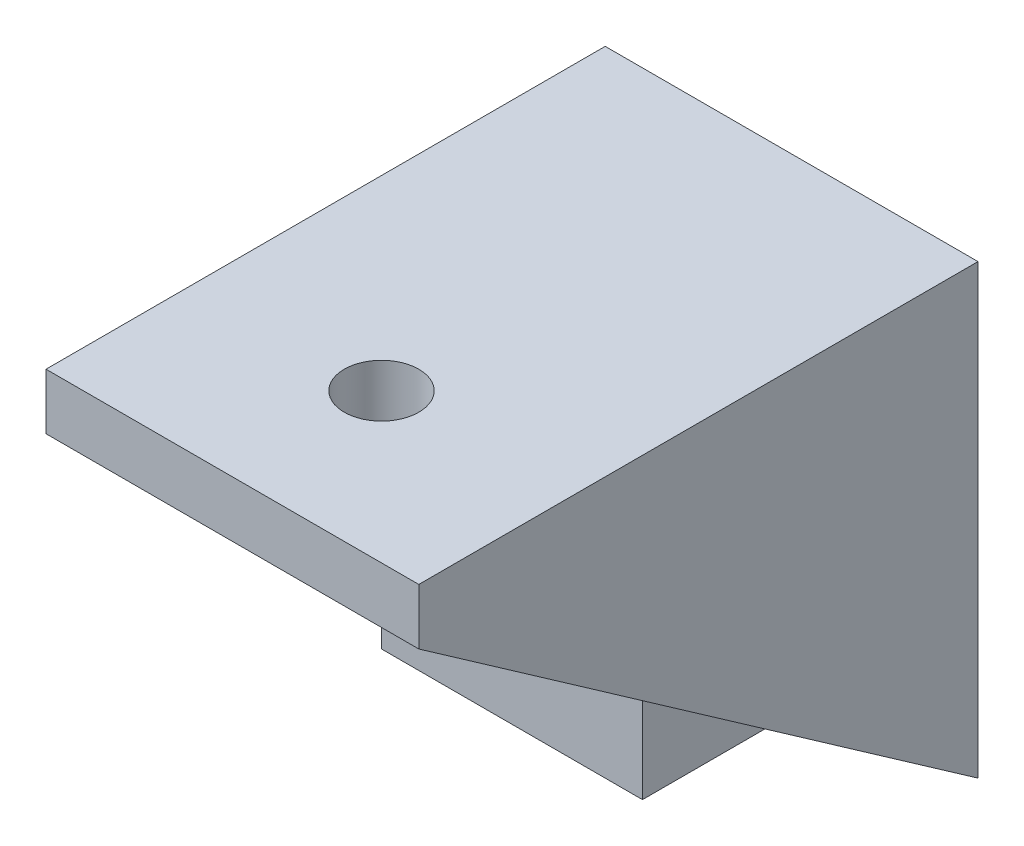
SolidWorks part; units mm, degrees
ref_plane "Front" through (0, 0, 0) normal (0, 0, 1) x (1, 0, 0)
ref_plane "Top" through (0, 0, 0) normal (0, 1, 0) x (1, 0, 0)
ref_plane "Right" through (0, 0, 0) normal (1, 0, 0) x (0, 0, -1)
sketch "Sketch1" plane through (0, 0, 0) normal (0, 0, 1) x (1, 0, 0)
  line L1 (-10, -12) -> (10, -12)
  line L2 (-10, -12) -> (-10, 12)
  line L3 (-10, 12) -> (10, 12)
  line L4 (10, -12) -> (10, 12)
  line L5 (-10, -12) -> (10, 12) construction
  line L6 (-10, 12) -> (10, -12) construction
  point P0 (0, 0)
  dimension "D1" = 24
  dimension "D2" = 20
extrude "Boss-Extrude1" add sketch "Sketch1" along normal blind 30
sketch "Sketch2" plane through (10, 0, 0) normal (1, 0, 0) x (0, 0, -1)
  line L0 (0, -12) -> (-30, 9)
  line L1 (-30, -12) -> (-30, 12) construction
  line L2 (-30, 12) -> (0, 12) construction
  line L3 (-30, 9) -> (-30, -12)
  line L4 (-30, -12) -> (0, -12)
  dimension "D1" = 3
extrude "Cut-Extrude1" cut sketch "Sketch2" against normal through all
sketch "Sketch3" plane through (0, 0, 30) normal (0, 0, 1) x (1, 0, 0)
  line L0 (-8, 10) -> (-8, -10)
  line L1 (-10, 12) -> (10, 12)
  line L2 (-10, 12) -> (-10, -12)
  line L3 (-10, -12) -> (10, -12)
  line L4 (10, 12) -> (10, -12)
  line L5 (-10, 12) -> (10, -12) construction
  line L6 (-10, -12) -> (10, 12) construction
  line L7 (-8, -10) -> (8, -10)
  line L8 (8, 10) -> (8, -10)
  line L9 (-8, 10) -> (8, 10)
  point P4 (0, 0)
  line M10 (-10, 9) -> (10, 9)
  dimension "D1" = 2
extrude "Cut-Extrude2" cut sketch "Sketch3" against normal blind 27 contours L8 L0 L7 M10
sketch "Sketch4" plane through (0, 0, 3) normal (0, 0, 1) x (1, 0, 0)
  line L1 (-7, -7) -> (7, -7)
  line L2 (-7, -7) -> (-7, 7)
  line L3 (-7, 7) -> (7, 7)
  line L4 (7, -7) -> (7, 7)
  line L5 (-7, -7) -> (7, 7) construction
  line L6 (-7, 7) -> (7, -7) construction
  point P0 (0, 0)
  dimension "D1" = 14
extrude "Boss-Extrude2" add sketch "Sketch4" along normal blind 12
sketch "Sketch5" plane through (0, 0, 0) normal (0, 0, -1) x (-1, 0, 0)
  circle A0 centre (0, 0) radius 1.6
  dimension "D1" = 3.2
extrude "Cut-Extrude3" cut sketch "Sketch5" against normal through all
sketch "Sketch6" plane through (0, 9, 0) normal (0, -1, 0) x (1, 0, 0)
  circle A0 centre (0, 22) radius 2
  point P2 (0, 0)
  dimension "D1" = 4
  dimension "D2" = 22
extrude "Cut-Extrude4" cut sketch "Sketch6" against normal through all
